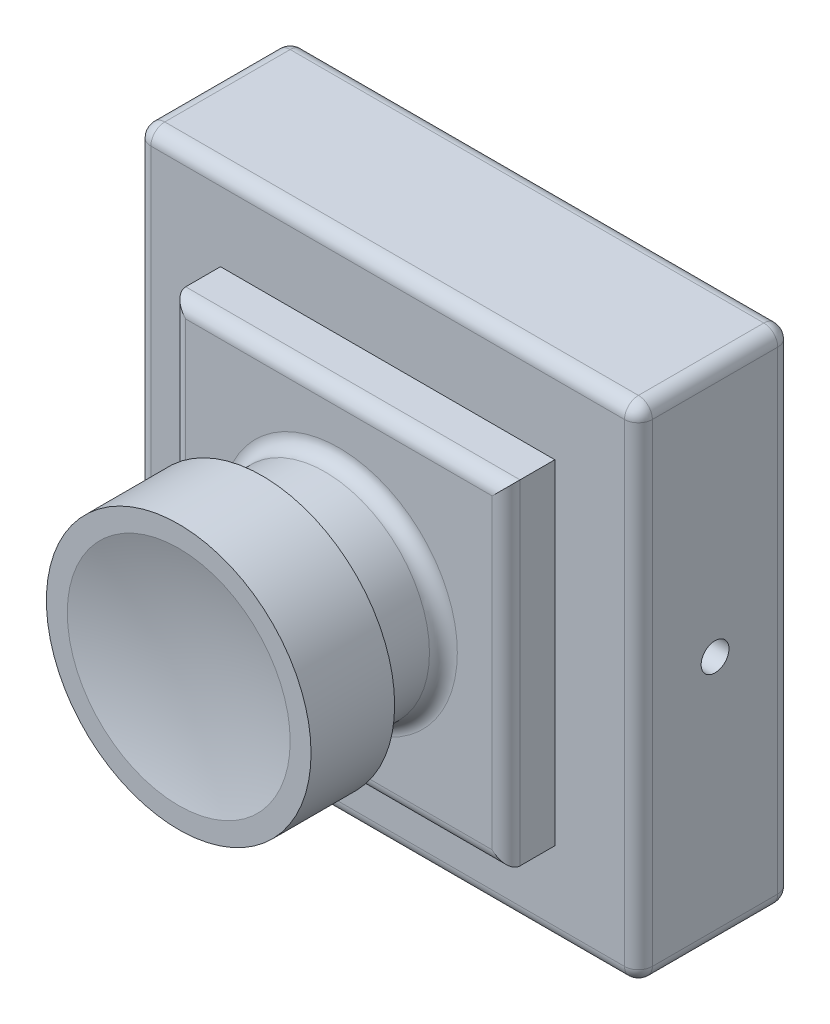
SolidWorks part; units mm, degrees
ref_plane "前视基准面" through (0, 0, 0) normal (0, 0, 1) x (1, 0, 0)
ref_plane "上视基准面" through (0, 0, 0) normal (0, 1, 0) x (1, 0, 0)
ref_plane "右视基准面" through (0, 0, 0) normal (1, 0, 0) x (0, 0, -1)
sketch "草图1" plane through (0, 0, 0) normal (0, 0, 1) x (1, 0, 0)
  line L1 (-18, -18) -> (18, -18)
  line L2 (-18, -18) -> (-18, 18)
  line L3 (-18, 18) -> (18, 18)
  line L4 (18, -18) -> (18, 18)
  line L5 (-18, -18) -> (18, 18) construction
  line L6 (-18, 18) -> (18, -18) construction
  point P0 (0, 0)
  dimension "D1" = 36
  dimension "D2" = 36
extrude "凸台-拉伸1" add sketch "草图1" along normal blind 11
sketch "草图2" plane through (0, 0, 11) normal (0, 0, 1) x (1, 0, 0)
  line L1 (12, -12) -> (-12, -12)
  line L2 (12, -12) -> (12, 12)
  line L3 (12, 12) -> (-12, 12)
  line L4 (-12, -12) -> (-12, 12)
  line L5 (12, -12) -> (-12, 12) construction
  line L6 (12, 12) -> (-12, -12) construction
  point P0 (0, 0)
  dimension "D1" = 24
  dimension "D2" = 24
extrude "凸台-拉伸2" add sketch "草图2" along normal blind 3.5
sketch "草图3" plane through (0, 0, 14.5) normal (0, 0, 1) x (1, 0, 0)
  circle A0 centre (0, 0) radius 7.5
  dimension "D1" = 15
extrude "凸台-拉伸3" add sketch "草图3" along normal blind 5.5
sketch "草图4" plane through (0, 0, 20) normal (0, 0, 1) x (1, 0, 0)
  circle A0 centre (0, 0) radius 9.5
  dimension "D1" = 19
extrude "凸台-拉伸4" add sketch "草图4" along normal blind 6
sketch "草图5" plane through (0, 0, 0) normal (0, 1, 0) x (1, 0, 0)
  line L0 (0, -24.9137) -> (0, -26)
  line L1 (-9.5, -26) -> (9.5, -26) construction
  line L2 (0, -24.3537) -> (0, -29.9792) construction
  line L3 (0, -26) -> (8, -26)
  arc A0 (8, -26) -> (0, -24.9137) centre (0, -54.9137) ccw
  dimension "D1" = 30
  dimension "D2" = 8
revolve "切除-旋转1" cut sketch "草图5" angle 360 about L2
fillet "圆角1" radius 1 17 edges at (0, 12, 14.5) (12, 0, 14.5) (0, -12, 14.5) (-12, 0, 14.5) (7.5, 0, 14.5) (0, -18, 11) (0, -18, 0) (-18, 0, 11) (-18, -18, 5.5) (-18, 0, 0) (18, -18, 5.5) (18, 0, 11) (18, 0, 0) (18, 18, 5.5) (0, 18, 11) (-18, 18, 5.5) (0, 18, 0)
sketch "草图6" plane through (18, 0, 0) normal (1, 0, 0) x (0, 0, -1)
  line L0 (0, 0) -> (-9.1622, 0) construction
  line L1 (0, 17) -> (0, -17) construction
  line L2 (-5.5, 14.626) -> (-5.5, -10.1) construction
  line L3 (-1, 17) -> (-10, 17) construction
  circle A0 centre (-5.5, 0) radius 1
  point P8 (-5.5, 14.626)
  point P11 (-5.5, 17)
  dimension "D1" = 2
extrude "切除-拉伸1" cut sketch "草图6" against normal blind 5
mirror "镜向1" about plane through (0, 0, 0) normal (1, 0, 0) of "切除-拉伸1"
sketch "草图7" plane through (0, 0, 0) normal (0, 0, -1) x (-1, 0, 0)
  line L0 (-14, 14) -> (0, 0) construction
  line L1 (17, 17) -> (-17, 17) construction
  line L2 (0, 0) -> (-21.3391, 0) construction
  line L3 (0, 0) -> (0, -22.6663) construction
  circle A0 centre (-14, 14) radius 1
  circle A1 centre (-14, -14) radius 1
  circle A2 centre (14, -14) radius 1
  circle A3 centre (14, 14) radius 1
  dimension "D1" = 2
  dimension "D2" = 14
  dimension "D3" = 45
extrude "切除-拉伸2" cut sketch "草图7" against normal blind 5
